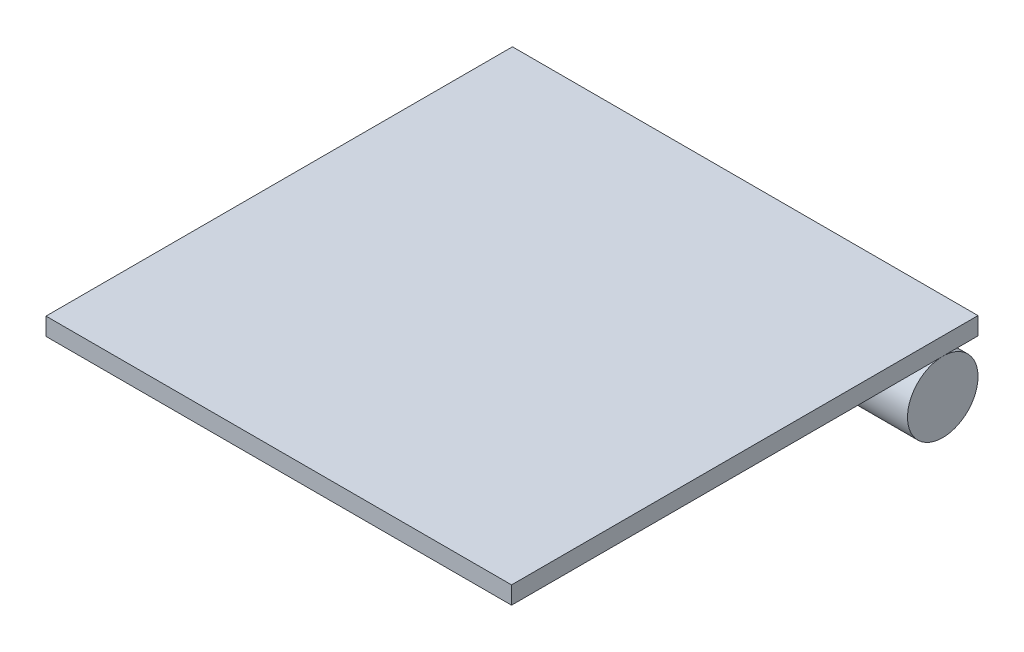
SolidWorks part; units mm, degrees
ref_plane "Ebene vorne" through (0, 0, 0) normal (0, 0, 1) x (1, 0, 0)
ref_plane "Ebene oben" through (0, 0, 0) normal (0, 1, 0) x (1, 0, 0)
ref_plane "Ebene rechts" through (0, 0, 0) normal (1, 0, 0) x (0, 0, -1)
sketch "Skizze1" plane through (0, 0, 0) normal (1, 0, 0) x (0, 0, -1)
  line L0 (0, 0) -> (132.334, 0)
  line L1 (132.334, 0) -> (132.334, 5)
  line L2 (132.334, 5) -> (0, 5)
  line L3 (0, 5) -> (0, 0)
  circle A0 centre (122.334, -10) radius 10
  dimension "D3" = 20
  dimension "D1" = 132.334
  dimension "D2" = 5
extrude "Aufsatz-Linear austragen1" add sketch "Skizze1" along normal blind 132.08 contours A0 | L2 L3 L0 L1
